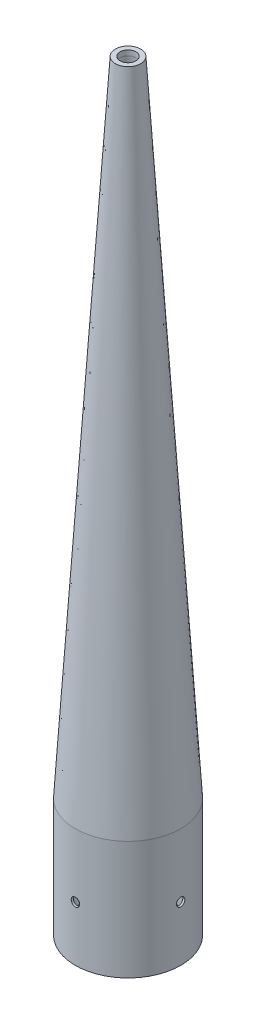
SolidWorks part; units mm, degrees
material "S-Glass Fiber"
ref_plane "Front Plane" through (0, 0, 0) normal (0, 0, 1) x (1, 0, 0)
ref_plane "Top Plane" through (0, 0, 0) normal (0, 1, 0) x (1, 0, 0)
ref_plane "Right Plane" through (0, 0, 0) normal (1, 0, 0) x (0, 0, -1)
sketch "Sketch1" plane through (0, 0, 0) normal (0, 0, 1) x (1, 0, 0)
  line L0 (0, 0) -> (-39.624, 0)
  line L3 (0, 635) -> (0, 0)
  line L4 (-39.624, 0) -> (0, 635)
  dimension "D1" = 39.624
  dimension "D2" = 635
revolve "Revolve1" add sketch "Sketch1" angle 360 about L3
ref_plane "Plane1" through (0, 482.6, 0) normal (0, 1, 0) x (1, 0, 0)
split "Split1" trim tools "Plane1" bodies to split 101 resulting bodies 102 103
shell "Shell1" thickness 3.81
sketch "Sketch2" plane through (0, 0, 0) normal (0, -1, 0) x (1, 0, 0)
  circle A0 centre (0, 0) radius 39.624
  dimension "D1" = 79.248
extrude "Boss-Extrude1" add sketch "Sketch2" along normal blind 88.9
sketch "Sketch4" plane through (0, -88.9, 0) normal (0, -1, 0) x (1, 0, 0)
  circle A0 centre (0, 0) radius 38.1
  dimension "D1" = 76.2
extrude "Cut-Extrude1" cut sketch "Sketch4" against normal blind 88.9
sketch "Sketch5" plane through (0, 482.6, 0) normal (0, 1, 0) x (1, 0, 0)
  circle A0 centre (0, 0) radius 34.5397
extrude "Cut-Extrude2" cut sketch "Sketch5" along normal through all
sketch "Sketch7" plane through (0, 478.79, 0) normal (0, -1, 0) x (-1, 0, 0)
  circle A0 centre (0, 0) radius 5.9301
  dimension "D1" = 11.8602
extrude "Cut-Extrude5" cut sketch "Sketch7" against normal through all
sketch "Sketch8" plane through (0, 0, 0) normal (1, 0, 0) x (0, 0, -1)
  line L2 (-39.624, -88.9) -> (39.624, -88.9) construction
  circle A0 centre (0, -47.625) radius 3.175
  point P2 (0, 0)
  dimension "D2" = 6.35
  dimension "D1" = 38.1
extrude "Cut-Extrude6" cut sketch "Sketch8" along normal through all
pattern_circular "CirPattern1" count 4 over 360 about axis through (0, -88.9, 0) along (0, 1, 0) of "Cut-Extrude6"
